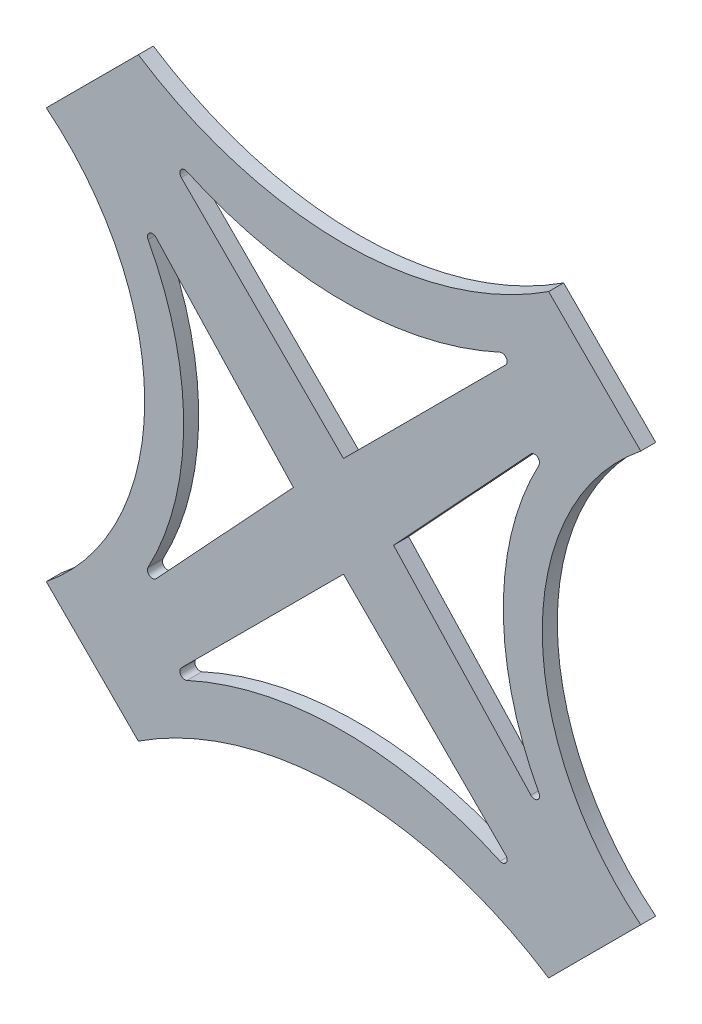
SolidWorks part; units mm, degrees
ref_plane "Front Plane" through (0, 0, 0) normal (0, 0, 1) x (1, 0, 0)
ref_plane "Top Plane" through (0, 0, 0) normal (0, 1, 0) x (1, 0, 0)
ref_plane "Right Plane" through (0, 0, 0) normal (1, 0, 0) x (0, 0, -1)
sketch "Sketch1" plane through (0, 0, 0) normal (0, 0, 1) x (1, 0, 0)
  line L1 (164.7, -164.7) -> (-164.7, -164.7) construction
  line L2 (164.7, -164.7) -> (164.7, 164.7) construction
  line L3 (164.7, 164.7) -> (-164.7, 164.7) construction
  line L4 (-164.7, -164.7) -> (-164.7, 164.7) construction
  line L5 (164.7, -164.7) -> (-164.7, 164.7) construction
  line L6 (164.7, 164.7) -> (-164.7, -164.7) construction
  line L11 (-164.7, 164.7) -> (-44.4918, 44.4918)
  line L12 (164.7, 164.7) -> (44.4918, 44.4918)
  line L16 (164.7, -164.7) -> (44.4918, -44.4918)
  line L17 (-164.7, -164.7) -> (-44.4918, -44.4918)
  circle A0 centre (-164.7, 164.7) radius 139.7 construction
  circle A1 centre (164.7, 164.7) radius 139.7 construction
  circle A2 centre (-164.7, -164.7) radius 139.7 construction
  circle A3 centre (164.7, -164.7) radius 139.7 construction
  circle A4 centre (-44.4918, 44.4918) radius 5
  circle A5 centre (44.4918, 44.4918) radius 5
  circle A6 centre (44.4918, -44.4918) radius 5
  circle A7 centre (-44.4918, -44.4918) radius 5
  point P0 (0, 0)
  point P10 (0, 0)
  dimension "D3" = 279.4
  dimension "D5" = 10
  dimension "D1" = 329.4
  dimension "D2" = 329.4
  dimension "D4" = 170
extrude "Boss-Extrude1" add sketch "Sketch1" along normal blind 0.1
sketch "Sketch2" plane through (0, 0, 0) normal (0, 0, 1) x (1, 0, 0)
  line L0 (-59.3411, 40.9563) -> (-40.9563, 59.3411)
  line L1 (-164.7, 164.7) -> (-44.4918, 44.4918) construction
  line L2 (164.7, 164.7) -> (-164.7, -164.7) construction
  line L3 (164.7, -164.7) -> (-164.7, 164.7) construction
  line L4 (164.7, 164.7) -> (-164.7, -164.7) construction
  line L5 (164.7, -164.7) -> (-164.7, 164.7) construction
  line L6 (40.9563, -59.3411) -> (59.3411, -40.9563)
  line L7 (0.055, 0) -> (-0.055, 0) construction
  line L8 (40.9563, 59.3411) -> (59.3411, 40.9563)
  line L9 (-59.3411, -40.9563) -> (-40.9563, -59.3411)
  line L10 (0, -0.055) -> (0, 0.055) construction
  line L15 (-32.3765, 42.3765) -> (0, 10)
  line L16 (0, 10) -> (32.3765, 42.3765)
  line L17 (-37.4101, 29.4957) -> (-10, 0)
  line L18 (10, 0) -> (37.4101, -29.4957)
  line L19 (37.4101, 29.4957) -> (10, 0)
  line L22 (-10, 0) -> (-37.4101, -29.4957)
  line L23 (0, -10) -> (32.3765, -42.3765)
  line L24 (-32.3765, -42.3765) -> (0, -10)
  arc A1 (-59.3411, 40.9563) -> (-59.3411, -40.9563) centre (-92.1866, 0) cw
  arc A3 (59.3411, 40.9563) -> (59.3411, -40.9563) centre (92.1866, 0) ccw
  arc A7 (-39.0241, 28.3426) -> (-39.0241, -28.3426) centre (-91.9079, 0) cw
  arc A8 (-37.4101, -29.4957) -> (-39.0241, -28.3426) centre (-38.1427, -28.815) cw
  arc A9 (-39.0241, 28.3426) -> (-37.4101, 29.4957) centre (-38.1427, 28.815) cw
  arc A10 (39.0241, 28.3426) -> (39.0241, -28.3426) centre (91.9079, 0) ccw
  arc A11 (37.4101, -29.4957) -> (39.0241, -28.3426) centre (38.1427, -28.815) ccw
  arc A12 (39.0241, 28.3426) -> (37.4101, 29.4957) centre (38.1427, 28.815) ccw
  arc A14 (-40.9563, 59.3411) -> (40.9563, 59.3411) centre (0, 122.1709) ccw
  arc A15 (31.2527, 43.9926) -> (-31.2527, 43.9926) centre (0, 112.1709) cw
  arc A16 (31.2527, 43.9926) -> (32.3765, 42.3765) centre (31.6694, 43.0836) cw
  arc A17 (-32.3765, 42.3765) -> (-31.2527, 43.9926) centre (-31.6694, 43.0836) cw
  arc A18 (-32.3765, -42.3765) -> (-31.2527, -43.9926) centre (-31.6694, -43.0836) ccw
  arc A19 (31.2527, -43.9926) -> (32.3765, -42.3765) centre (31.6694, -43.0836) ccw
  arc A20 (31.2527, -43.9926) -> (-31.2527, -43.9926) centre (0, -112.1709) ccw
  arc A21 (-40.9563, -59.3411) -> (40.9563, -59.3411) centre (0, -122.1709) cw
  point P4 (-50.1487, 50.1487)
  point P25 (-36.8454, 46.8454)
  point P26 (36.8454, 46.8454)
  point P27 (45.0798, 41.0755)
  point P29 (45.0798, -41.0755)
  point P30 (36.8454, -46.8454)
  point P32 (-36.8454, -46.8454)
  point P33 (-47.956, -40.8441)
  point P35 (-47.956, 40.8441)
  point P45 (-31.9079, 0)
  dimension "D3" = 52.5
  dimension "D4" = 75
  dimension "D8" = 60
  dimension "D5" = 75
  dimension "D9" = 1
  dimension "D12" = 1
  dimension "D1" = 26
  dimension "D2" = 8
  dimension "D6" = 10
  dimension "D7" = 10
  dimension "D10" = 90
  dimension "D11" = 10
extrude "Boss-Extrude2" add sketch "Sketch2" along normal blind 3
sketch "Sketch3" plane through (0, 0, 3) normal (0, 0, 1) x (1, 0, 0)
  line L1 (44.5, -41.5) -> (-44.5, -41.5) construction
  line L2 (44.5, -41.5) -> (44.5, 41.5) construction
  line L3 (44.5, 41.5) -> (-44.5, 41.5) construction
  line L4 (-44.5, -41.5) -> (-44.5, 41.5) construction
  line L5 (44.5, -41.5) -> (-44.5, 41.5) construction
  line L6 (44.5, 41.5) -> (-44.5, -41.5) construction
  circle A0 centre (-44.5, -41.5) radius 3
  circle A1 centre (44.5, -41.5) radius 3
  circle A2 centre (44.5, 41.5) radius 3
  circle A3 centre (-44.5, 41.5) radius 3
  point P0 (0, 0)
  dimension "D4" = 6
  dimension "D1" = 89
  dimension "D2" = 89
  dimension "D3" = 83
extrude "Cut-Extrude1" [suppressed] cut sketch "Sketch3" against normal blind 3
